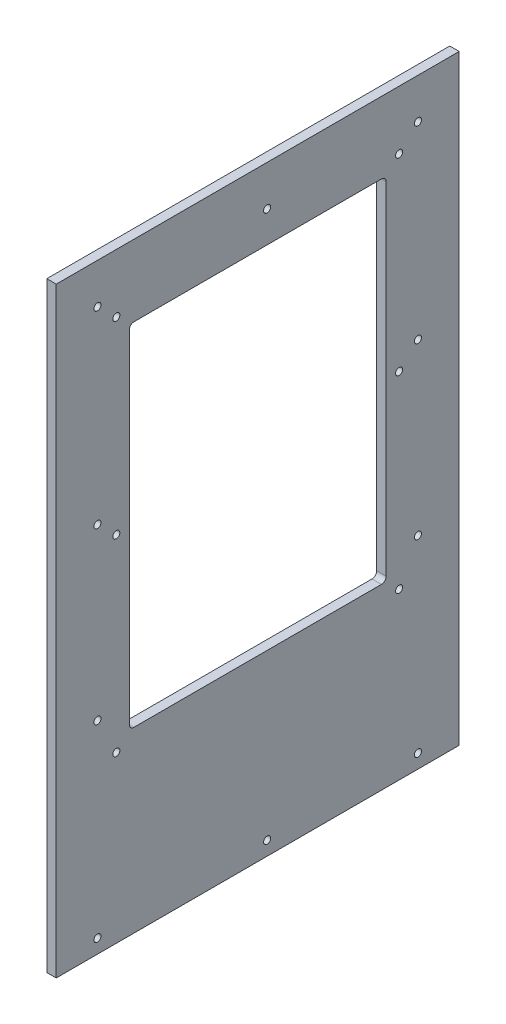
SolidWorks part; units mm, degrees
material "PVC Rigid"
ref_plane "Front Plane" through (0, 0, 0) normal (0, 0, 1) x (1, 0, 0)
ref_plane "Top Plane" through (0, 0, 0) normal (0, 1, 0) x (1, 0, 0)
ref_plane "Right Plane" through (0, 0, 0) normal (1, 0, 0) x (0, 0, -1)
sketch "Sketch1" plane through (0, 0, 0) normal (1, 0, 0) x (0, 0, -1)
  line L1 (-271.4625, -404.8125) -> (271.4625, -404.8125)
  line L2 (-271.4625, -404.8125) -> (-271.4625, 404.8125)
  line L3 (-271.4625, 404.8125) -> (271.4625, 404.8125)
  line L4 (271.4625, -404.8125) -> (271.4625, 404.8125)
  line L5 (-271.4625, -404.8125) -> (271.4625, 404.8125) construction
  line L6 (-271.4625, 404.8125) -> (271.4625, -404.8125) construction
  point P0 (0, 0)
  dimension "D1" = 542.925
  dimension "D2" = 809.625
extrude "Boss-Extrude1" add sketch "Sketch1" along normal blind 12.7
sketch "Sketch2" plane through (12.7, 0, 0) normal (1, 0, 0) x (0, 0, -1)
  line L0 (0, -17.78) -> (0, -404.8125) construction
  line L1 (-215.9, -386.08) -> (215.9, -386.08) construction
  line L2 (-215.9, -386.08) -> (-215.9, 350.52) construction
  line L3 (-215.9, 350.52) -> (215.9, 350.52) construction
  line L4 (215.9, -386.08) -> (215.9, 350.52) construction
  line L5 (-215.9, -386.08) -> (215.9, 350.52) construction
  line L6 (-215.9, 350.52) -> (215.9, -386.08) construction
  line L7 (-271.4625, -404.8125) -> (271.4625, -404.8125) construction
  circle A0 centre (-215.9, 350.52) radius 4.7625
  circle A1 centre (215.9, 350.52) radius 4.7625
  circle A2 centre (-215.9, -386.08) radius 4.7625
  circle A3 centre (215.9, -386.08) radius 4.7625
  point P0 (0, -17.78)
  dimension "D1" = 9.525
  dimension "D2" = 9.525
  dimension "D3" = 9.525
  dimension "D4" = 9.525
  dimension "D5" = 431.8
  dimension "D6" = 736.6
  dimension "D7" = 18.7325
extrude "Cut-Extrude1" cut sketch "Sketch2" against normal blind 12.7
sketch "Sketch3" plane through (12.7, 0, 0) normal (1, 0, 0) x (0, 0, -1)
  line L0 (0, 350.52) -> (0, -386.08) construction
  line L1 (-215.9, 350.52) -> (215.9, 350.52) construction
  line L2 (-215.9, 350.52) -> (-215.9, -386.08) construction
  line L3 (-215.9, -386.08) -> (215.9, -386.08) construction
  line L4 (215.9, 350.52) -> (215.9, -386.08) construction
  circle A0 centre (-215.9, 96.52) radius 4.7625
  circle A1 centre (-215.9, -132.08) radius 4.7625
  circle A2 centre (12.7, 350.52) radius 4.7625
  circle A3 centre (12.7, -386.08) radius 4.7625
  circle A4 centre (215.9, -132.08) radius 4.7625
  circle A5 centre (215.9, 96.52) radius 4.7625
  dimension "D1" = 9.525
  dimension "D2" = 9.525
  dimension "D3" = 9.525
  dimension "D4" = 9.525
  dimension "D5" = 254
  dimension "D6" = 254
  dimension "D7" = 203.2
  dimension "D8" = 203.2
extrude "Cut-Extrude2" cut sketch "Sketch3" against normal blind 12.7
sketch "Sketch6" plane through (0, 0, 0) normal (-1, 0, 0) x (0, 0, 1)
  circle A0 centre (-190.5, 325.9137) radius 4.7625
  circle A1 centre (190.5, 325.9137) radius 4.7625
  circle A2 centre (-190.5, -182.0863) radius 4.7625
  circle A3 centre (190.5, -182.0863) radius 4.7625
extrude "Cut-Extrude4" cut sketch "Sketch6" against normal blind 12.7
sketch "Sketch7" plane through (0, 0, 0) normal (-1, 0, 0) x (0, 0, 1)
  circle A0 centre (-190.5, 71.9138) radius 4.7625
  circle A1 centre (190.5, 71.9138) radius 4.7625
extrude "Cut-Extrude5" cut sketch "Sketch7" against normal blind 12.7
sketch "Sketch9" plane through (12.7, 0, 0) normal (1, 0, 0) x (0, 0, -1)
  line L0 (0, 308.4513) -> (0, -164.6238) construction
  line L1 (-173.0375, 308.4513) -> (173.0375, 308.4513)
  line L2 (-173.0375, 308.4513) -> (-173.0375, -164.6238)
  line L3 (-173.0375, -164.6238) -> (173.0375, -164.6238)
  line L4 (173.0375, 308.4513) -> (173.0375, -164.6238)
  line L6 (-190.5, -182.0862) -> (190.5, -182.0862) construction
  line L7 (-190.5, -182.0862) -> (-190.5, 325.9138) construction
  line L8 (-190.5, 325.9138) -> (190.5, 325.9138) construction
  line L9 (190.5, -182.0862) -> (190.5, 325.9138) construction
  line L10 (-190.5, -182.0862) -> (190.5, 325.9138) construction
  line L11 (-190.5, 325.9138) -> (190.5, -182.0862) construction
  circle A0 centre (-190.5, 325.9137) radius 4.7625 construction
  circle A1 centre (-190.5, -182.0863) radius 4.7625 construction
  circle A3 centre (190.5, 71.9138) radius 4.7625 construction
  point P8 (0, 71.9137)
  dimension "D1" = 17.4625
  dimension "D2" = 17.4625
  dimension "D3" = 17.4625
  dimension "D4" = 381
  dimension "D5" = 508
extrude "Cut-Extrude6" cut sketch "Sketch9" against normal blind 12.7
fillet "Fillet1" radius 6.35 4 edges at (6.35, 308.4513, 173.0375) (6.35, 308.4513, -173.0375) (6.35, -164.6238, -173.0375) (6.35, -164.6238, 173.0375)
